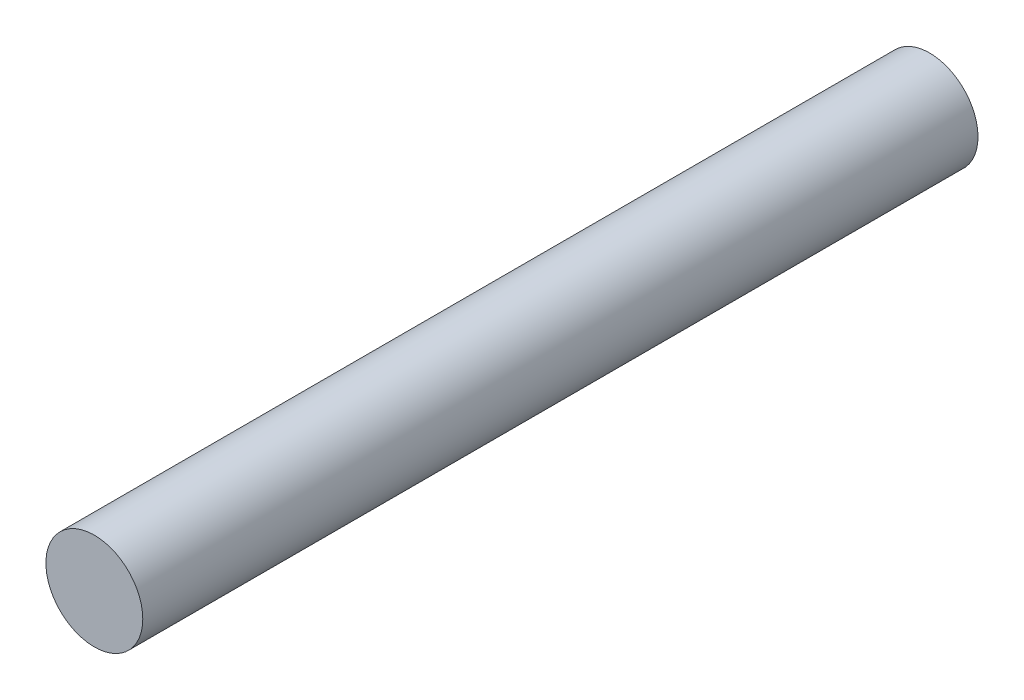
SolidWorks part; units mm, degrees
ref_plane "Спереди" through (0, 0, 0) normal (0, 0, 1) x (1, 0, 0)
ref_plane "Сверху" through (0, 0, 0) normal (0, 1, 0) x (1, 0, 0)
ref_plane "Справа" through (0, 0, 0) normal (1, 0, 0) x (0, 0, -1)
sketch "Эскиз1" plane through (0, 0, 0) normal (0, 0, 1) x (1, 0, 0)
  circle A0 centre (-19.7286, -1.8595) radius 10.7294
extrude "Бобышка-Вытянуть1" add sketch "Эскиз1" along normal blind 185
